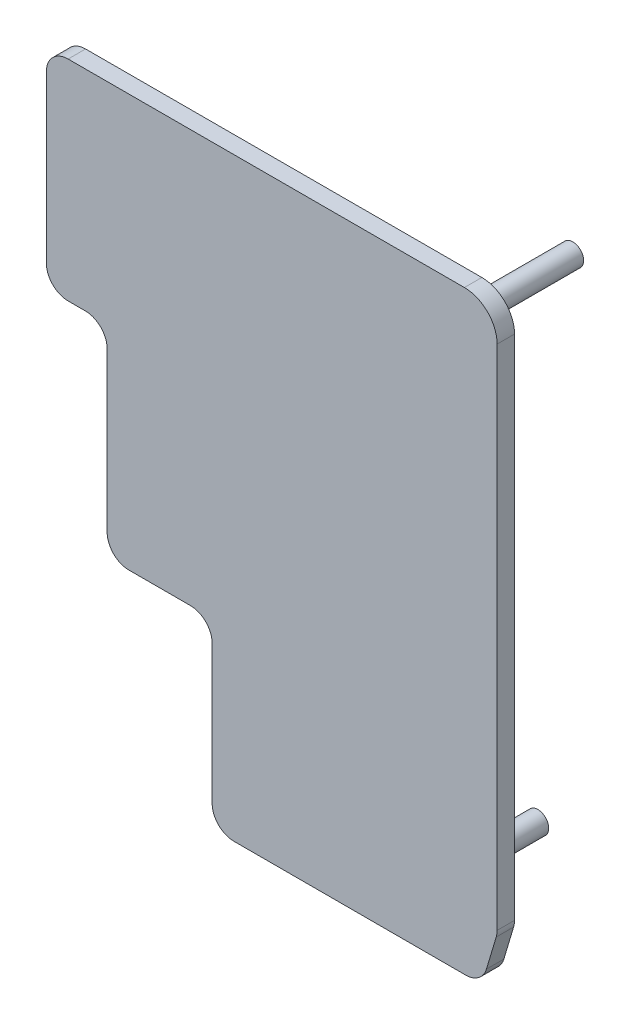
SolidWorks part; units mm, degrees
ref_plane "Front Plane" through (0, 0, 0) normal (0, 0, 1) x (1, 0, 0)
ref_plane "Top Plane" through (0, 0, 0) normal (0, 1, 0) x (1, 0, 0)
ref_plane "Right Plane" through (0, 0, 0) normal (1, 0, 0) x (0, 0, -1)
sketch "Sketch1" plane through (0, 0, 0) normal (0, 0, 1) x (1, 0, 0)
  line L0 (27.2458, 41.5914) -> (27.2458, 22.3514)
  line L1 (27.2458, 22.3514) -> (32.8273, 22.3514)
  line L2 (32.8273, 22.3514) -> (32.8273, 3.7454)
  line L3 (32.8273, 3.7454) -> (42.4686, 3.7454)
  line L4 (42.4686, 3.7454) -> (42.4686, -13.0001)
  line L5 (42.4686, -13.0001) -> (67.2265, -13.0001)
  line L6 (67.2265, -13.0001) -> (68.6325, -8.2952)
  line L7 (27.2458, 41.5914) -> (65.6306, 41.616)
  line L8 (68.6325, -8.2952) -> (68.6325, 38.616)
  arc A0 (68.6325, 38.616) -> (65.6306, 41.616) centre (65.6325, 38.616) ccw
  line B0 (65.6306, 41.616) -> (-84.329, 41.5199)
  line B1 (-87.3271, 38.5295) -> (-87.5579, -33.4724)
  line B2 (-84.5579, -36.4821) -> (-37.7883, -36.4821)
  line B3 (-37.5372, -36.4926) -> (7.4572, -40.2715)
  line B4 (7.7082, -40.2821) -> (55.9702, -40.2821)
  line B5 (58.8163, -38.2307) -> (68.4785, -9.2439)
  line B6 (68.6325, -8.2952) -> (68.6325, 38.616)
  line B7 (-84.5675, 23.2679) -> (-69.0675, 23.2679)
  line B8 (-69.0675, 23.2679) -> (-69.0675, 38.7679)
  line B9 (-69.0675, 38.7679) -> (-84.5675, 38.7679)
  line B10 (-84.5675, 38.7679) -> (-84.5675, 23.2679)
  line B11 (-65.5675, 23.2679) -> (-50.0675, 23.2679)
  line B12 (-50.0675, 23.2679) -> (-50.0675, 38.7679)
  line B13 (-50.0675, 38.7679) -> (-65.5675, 38.7679)
  line B14 (-65.5675, 38.7679) -> (-65.5675, 23.2679)
  line B15 (-46.5675, 23.2679) -> (-31.0675, 23.2679)
  line B16 (-31.0675, 23.2679) -> (-31.0675, 38.7679)
  line B17 (-31.0675, 38.7679) -> (-46.5675, 38.7679)
  line B18 (-46.5675, 38.7679) -> (-46.5675, 23.2679)
  line B19 (-27.5675, 23.2679) -> (-12.0675, 23.2679)
  line B20 (-12.0675, 23.2679) -> (-12.0675, 38.7679)
  line B21 (-12.0675, 38.7679) -> (-27.5675, 38.7679)
  line B22 (-27.5675, 38.7679) -> (-27.5675, 23.2679)
  line B23 (-8.5675, 23.2679) -> (6.9325, 23.2679)
  line B24 (6.9325, 23.2679) -> (6.9325, 38.7679)
  line B25 (6.9325, 38.7679) -> (-8.5675, 38.7679)
  line B26 (-8.5675, 38.7679) -> (-8.5675, 23.2679)
  line B27 (10.4325, 23.2679) -> (25.9325, 23.2679)
  line B28 (25.9325, 23.2679) -> (25.9325, 38.7679)
  line B29 (25.9325, 38.7679) -> (10.4325, 38.7679)
  line B30 (10.4325, 38.7679) -> (10.4325, 23.2679)
  line B31 (-82.1925, 4.2679) -> (-66.6925, 4.2679)
  line B32 (-66.6925, 4.2679) -> (-66.6925, 19.7679)
  line B33 (-66.6925, 19.7679) -> (-82.1925, 19.7679)
  line B34 (-82.1925, 19.7679) -> (-82.1925, 4.2679)
  line B35 (-60.8175, 4.2679) -> (-45.3175, 4.2679)
  line B36 (-45.3175, 4.2679) -> (-45.3175, 19.7679)
  line B37 (-45.3175, 19.7679) -> (-60.8175, 19.7679)
  line B38 (-60.8175, 19.7679) -> (-60.8175, 4.2679)
  line B39 (-41.8175, 4.2679) -> (-26.3175, 4.2679)
  line B40 (-26.3175, 4.2679) -> (-26.3175, 19.7679)
  line B41 (-26.3175, 19.7679) -> (-41.8175, 19.7679)
  line B42 (-41.8175, 19.7679) -> (-41.8175, 4.2679)
  line B43 (-22.8175, 4.2679) -> (-7.3175, 4.2679)
  line B44 (-7.3175, 4.2679) -> (-7.3175, 19.7679)
  line B45 (-7.3175, 19.7679) -> (-22.8175, 19.7679)
  line B46 (-22.8175, 19.7679) -> (-22.8175, 4.2679)
  line B47 (-3.8175, 4.2679) -> (11.6825, 4.2679)
  line B48 (11.6825, 4.2679) -> (11.6825, 19.7679)
  line B49 (11.6825, 19.7679) -> (-3.8175, 19.7679)
  line B50 (-3.8175, 19.7679) -> (-3.8175, 4.2679)
  line B51 (15.1825, 4.2679) -> (30.6825, 4.2679)
  line B52 (30.6825, 4.2679) -> (30.6825, 19.7679)
  line B53 (30.6825, 19.7679) -> (15.1825, 19.7679)
  line B54 (15.1825, 19.7679) -> (15.1825, 4.2679)
  line B55 (-77.4425, -14.7321) -> (-61.9425, -14.7321)
  line B56 (-61.9425, -14.7321) -> (-61.9425, 0.7679)
  line B57 (-61.9425, 0.7679) -> (-77.4425, 0.7679)
  line B58 (-77.4425, 0.7679) -> (-77.4425, -14.7321)
  line B59 (-51.3175, -14.7321) -> (-35.8175, -14.7321)
  line B60 (-35.8175, -14.7321) -> (-35.8175, 0.7679)
  line B61 (-35.8175, 0.7679) -> (-51.3175, 0.7679)
  line B62 (-51.3175, 0.7679) -> (-51.3175, -14.7321)
  line B63 (-32.3175, -14.7321) -> (-16.8175, -14.7321)
  line B64 (-16.8175, -14.7321) -> (-16.8175, 0.7679)
  line B65 (-16.8175, 0.7679) -> (-32.3175, 0.7679)
  line B66 (-32.3175, 0.7679) -> (-32.3175, -14.7321)
  line B67 (-13.3175, -14.7321) -> (2.1825, -14.7321)
  line B68 (2.1825, -14.7321) -> (2.1825, 0.7679)
  line B69 (2.1825, 0.7679) -> (-13.3175, 0.7679)
  line B70 (-13.3175, 0.7679) -> (-13.3175, -14.7321)
  line B71 (5.6825, -14.7321) -> (21.1825, -14.7321)
  line B72 (21.1825, -14.7321) -> (21.1825, 0.7679)
  line B73 (21.1825, 0.7679) -> (5.6825, 0.7679)
  line B74 (5.6825, 0.7679) -> (5.6825, -14.7321)
  line B75 (24.6825, -14.7321) -> (40.1825, -14.7321)
  line B76 (40.1825, -14.7321) -> (40.1825, 0.7679)
  line B77 (40.1825, 0.7679) -> (24.6825, 0.7679)
  line B78 (24.6825, 0.7679) -> (24.6825, -14.7321)
  line B79 (-82.1925, -33.7321) -> (-66.6925, -33.7321)
  line B80 (-66.6925, -33.7321) -> (-66.6925, -18.2321)
  line B81 (-66.6925, -18.2321) -> (-82.1925, -18.2321)
  line B82 (-82.1925, -18.2321) -> (-82.1925, -33.7321)
  line B83 (-58.5375, -33.7321) -> (-43.0375, -33.7321)
  line B84 (-43.0375, -33.7321) -> (-43.0375, -18.2321)
  line B85 (-43.0375, -18.2321) -> (-58.5375, -18.2321)
  line B86 (-58.5375, -18.2321) -> (-58.5375, -33.7321)
  line B87 (6.1325, -37.5321) -> (21.6325, -37.5321)
  line B88 (21.6325, -37.5321) -> (21.6325, -22.0321)
  line B89 (21.6325, -22.0321) -> (6.1325, -22.0321)
  line B90 (6.1325, -22.0321) -> (6.1325, -37.5321)
  line B91 (35.1325, -37.5321) -> (50.6325, -37.5321)
  line B92 (50.6325, -37.5321) -> (50.6325, -22.0321)
  line B93 (50.6325, -22.0321) -> (35.1325, -22.0321)
  line B94 (35.1325, -22.0321) -> (35.1325, -37.5321)
  arc B95 (-84.329, 41.5199) -> (-87.3271, 38.5295) centre (-84.3271, 38.5199) ccw
  arc B96 (-87.5579, -33.4724) -> (-84.5579, -36.4821) centre (-84.5579, -33.4821) ccw
  arc B97 (-37.5372, -36.4926) -> (-37.7883, -36.4821) centre (-37.7883, -39.4821) ccw
  arc B98 (7.4572, -40.2715) -> (7.7082, -40.2821) centre (7.7082, -37.2821) ccw
  arc B99 (55.9702, -40.2821) -> (58.8163, -38.2307) centre (55.9702, -37.2821) ccw
  arc B100 (68.4785, -9.2439) -> (68.6325, -8.2952) centre (65.6325, -8.2952) ccw
  arc B101 (68.6325, 38.616) -> (65.6306, 41.616) centre (65.6325, 38.616) ccw
  circle B102 centre (-31.7875, -20.2821) radius 2.5
  circle B103 centre (-5.1175, -25.0321) radius 2.5
  circle B104 centre (31.4825, 36.7179) radius 2.5
  circle B105 centre (-82.9925, -6.9821) radius 2.5
  circle B106 centre (45.7325, -6.9821) radius 2.5
  circle B107 centre (-63.5175, 19.6179) radius 2.5
  circle B108 centre (-31.7875, -20.2821) radius 1
  circle B109 centre (-5.1175, -25.0321) radius 1
  circle B110 centre (31.4825, 36.7179) radius 1
  circle B111 centre (-82.9925, -6.9821) radius 1
  circle B112 centre (45.7325, -6.9821) radius 1
  circle B113 centre (-63.5175, 19.6179) radius 1
  line B114 (65.4624, 45.4806) -> (-84.4972, 45.3845)
  line B115 (-91.4926, 38.4069) -> (-91.7234, -33.595)
  line B116 (-84.7234, -40.6174) -> (-37.9958, -40.6174)
  line B117 (-37.9958, -40.6174) -> (6.9568, -44.3929)
  line B118 (7.5427, -44.4174) -> (55.8046, -44.4174)
  line B119 (62.4454, -39.631) -> (72.1077, -10.6442)
  line B120 (72.4669, -8.4306) -> (72.4669, 38.4806)
  line B121 (65.4644, 42.4806) -> (-84.4952, 42.3845)
  line B122 (-88.4926, 38.3973) -> (-88.7234, -33.6046)
  line B123 (-84.7234, -37.6174) -> (-37.9538, -37.6174)
  line B124 (-37.7865, -37.6244) -> (7.2079, -41.4034)
  line B125 (7.5427, -41.4174) -> (55.8046, -41.4174)
  line B126 (59.5994, -38.6823) -> (69.2617, -9.6955)
  line B127 (69.4669, -8.4306) -> (69.4669, 38.4806)
  arc B128 (-84.4972, 45.3845) -> (-91.4926, 38.4069) centre (-84.4927, 38.3845) ccw
  arc B129 (-91.7234, -33.595) -> (-84.7234, -40.6174) centre (-84.7234, -33.6174) ccw
  arc B130 (6.9568, -44.3929) -> (7.5427, -44.4174) centre (7.5427, -37.4174) ccw
  arc B131 (55.8046, -44.4174) -> (62.4454, -39.631) centre (55.8046, -37.4174) ccw
  arc B132 (72.1077, -10.6442) -> (72.4669, -8.4306) centre (65.4669, -8.4306) ccw
  arc B133 (72.4669, 38.4806) -> (65.4624, 45.4806) centre (65.4669, 38.4806) ccw
  circle B134 centre (-31.9531, -20.4174) radius 1
  circle B135 centre (-5.2831, -25.1674) radius 1
  circle B136 centre (31.3169, 36.5826) radius 1
  circle B137 centre (-83.1581, -7.1174) radius 1
  circle B138 centre (45.5669, -7.1174) radius 1
  circle B139 centre (-63.6831, 19.4826) radius 1
  arc B140 (-84.4952, 42.3845) -> (-88.4926, 38.3973) centre (-84.4927, 38.3845) ccw
  arc B141 (-88.7234, -33.6046) -> (-84.7234, -37.6174) centre (-84.7234, -33.6174) ccw
  arc B142 (-37.7865, -37.6244) -> (-37.9538, -37.6174) centre (-37.9538, -39.6174) ccw
  arc B143 (7.2079, -41.4034) -> (7.5427, -41.4174) centre (7.5427, -37.4174) ccw
  arc B144 (55.8046, -41.4174) -> (59.5994, -38.6823) centre (55.8046, -37.4174) ccw
  arc B145 (69.2617, -9.6955) -> (69.4669, -8.4306) centre (65.4669, -8.4306) ccw
  arc B146 (69.4669, 38.4806) -> (65.4644, 42.4806) centre (65.4669, 38.4806) ccw
sketch_block_instance "realBoard-1"
sketch_block "realBoard"
sketch_block_instance "wall_outline (1)-1"
sketch_block "wall_outline (1)"
extrude "Boss-Extrude1" add sketch "Sketch1" along normal blind 1.6 contours L8 A0 L7 L0 L1 L2 L3 L4 L5 L6 B106 B104 | B104 B136 B110 | B110 B136 | B110 B136 | B136 B110 | B106 B138 B112 | B112 B138 | B138 B112 | B112 B138
sketch "Sketch2" plane through (0, 0, 0) normal (0, 0, -1) x (-1, 0, 0)
  circle A0 centre (-30.5369, 26.3221) radius 1
  circle A1 centre (-45.8276, -10.7396) radius 1
  circle A2 centre (-61.7736, -8.1184) radius 1
  circle A3 centre (-64.9773, 38.6275) radius 1
  point P8 (-61.7736, -8.1184)
extrude "Boss-Extrude2" add sketch "Sketch2" along normal blind 9
fillet "Fillet1" radius 2 8 edges at (32.8273, 22.3514, 0.8) (42.4686, 3.7454, 0.8) (68.6325, -8.2952, 0.8) (67.2265, -13.0001, 0.8) (27.2458, 41.5914, 0.8) (42.4686, -13.0001, 0.8) (32.8273, 3.7454, 0.8) (27.2458, 22.3514, 0.8)
